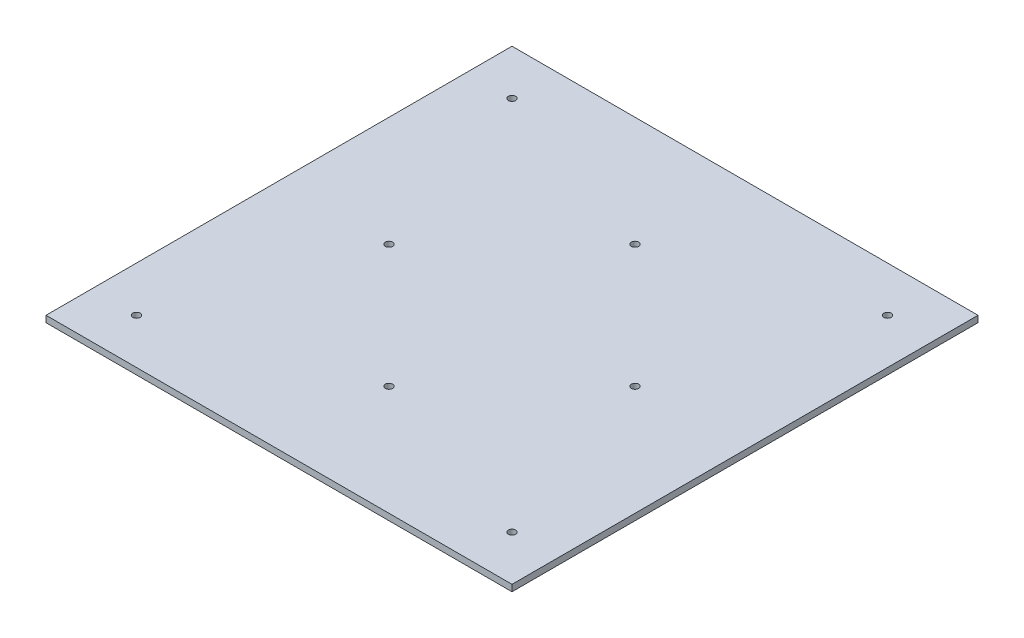
SolidWorks part; units mm, degrees
ref_plane "Front Plane" through (0, 0, 0) normal (0, 0, 1) x (1, 0, 0)
ref_plane "Top Plane" through (0, 0, 0) normal (0, 1, 0) x (1, 0, 0)
ref_plane "Right Plane" through (0, 0, 0) normal (1, 0, 0) x (0, 0, -1)
sketch "Sketch1" plane through (0, 0, 0) normal (0, 1, 0) x (1, 0, 0)
  line L1 (-107.95, -107.95) -> (107.95, -107.95)
  line L2 (-107.95, -107.95) -> (-107.95, 107.95)
  line L3 (-107.95, 107.95) -> (107.95, 107.95)
  line L4 (107.95, -107.95) -> (107.95, 107.95)
  line L5 (-107.95, -107.95) -> (107.95, 107.95) construction
  line L6 (-107.95, 107.95) -> (107.95, -107.95) construction
  point P0 (0, 0)
  dimension "D1" = 215.9
extrude "Boss-Extrude1" add sketch "Sketch1" along normal mid plane 3
sketch "Sketch3" plane through (0, 1.5, 0) normal (0, 1, 0) x (1, 0, 0)
  line L0 (-87, 0) -> (0, 0) construction
  line L1 (-127, -127) -> (127, -127) construction
  line L2 (-127, -127) -> (-127, 127) construction
  line L3 (-127, 127) -> (127, 127) construction
  line L4 (127, -127) -> (127, 127) construction
  line L5 (-127, -127) -> (127, 127) construction
  line L6 (-127, 127) -> (127, -127) construction
  line L7 (87, -87) -> (-87, -87) construction
  line L8 (87, -87) -> (87, 87) construction
  line L9 (87, 87) -> (-87, 87) construction
  line L10 (-87, -87) -> (-87, 87) construction
  line L11 (87, -87) -> (-87, 87) construction
  line L12 (87, 87) -> (-87, -87) construction
  line L13 (0, 0) -> (87, 0) construction
  line L14 (0, 87) -> (0, 0) construction
  line L15 (0, 0) -> (0, -87) construction
  point P0 (0, 0)
  point P6 (0, 0)
  point P15 (-57, 0)
  point P17 (0, 57)
  point P18 (57, 0)
  point P19 (0, -57)
  dimension "D1" = 254
  dimension "D2" = 40
  dimension "D3" = 70
  dimension "D4" = 70
  dimension "D5" = 70
  dimension "D6" = 70
hole_wizard "M3 Clearance Hole1" positions "3DSketch1" profile "Sketch4" hole size "M3" standard "ANSI Metric"
sketch3d "3DSketch1"
  point P0 (-87, 1.5, -87)
  point P3 (0, 1.5, -57)
  point P6 (87, 1.5, -87)
  point P9 (57, 1.5, 0)
  point P12 (87, 1.5, 87)
  point P15 (0, 1.5, 57)
  point P18 (-87, 1.5, 87)
  point P21 (-57, 1.5, 0)
sketch "Sketch4" plane through (-87, 1.5, -87) normal (1, 0, 0) x (0, 0, 1)
  line L0 (0, 0) -> (0, 11.0215)
  line L1 (0, 11.0215) -> (1.7, 10)
  line L2 (1.7, 10) -> (1.7, 0)
  line L5 (1.7, 0) -> (0, 0)
  line L10 (0, 11.0215) -> (-1.7, 10) construction
  line L11 (0, -6.35) -> (0, 107.95) construction
  dimension "Hole Dia." = 3.4
  dimension "Hole Depth" = 10
  dimension "Drill Angle" = 118
